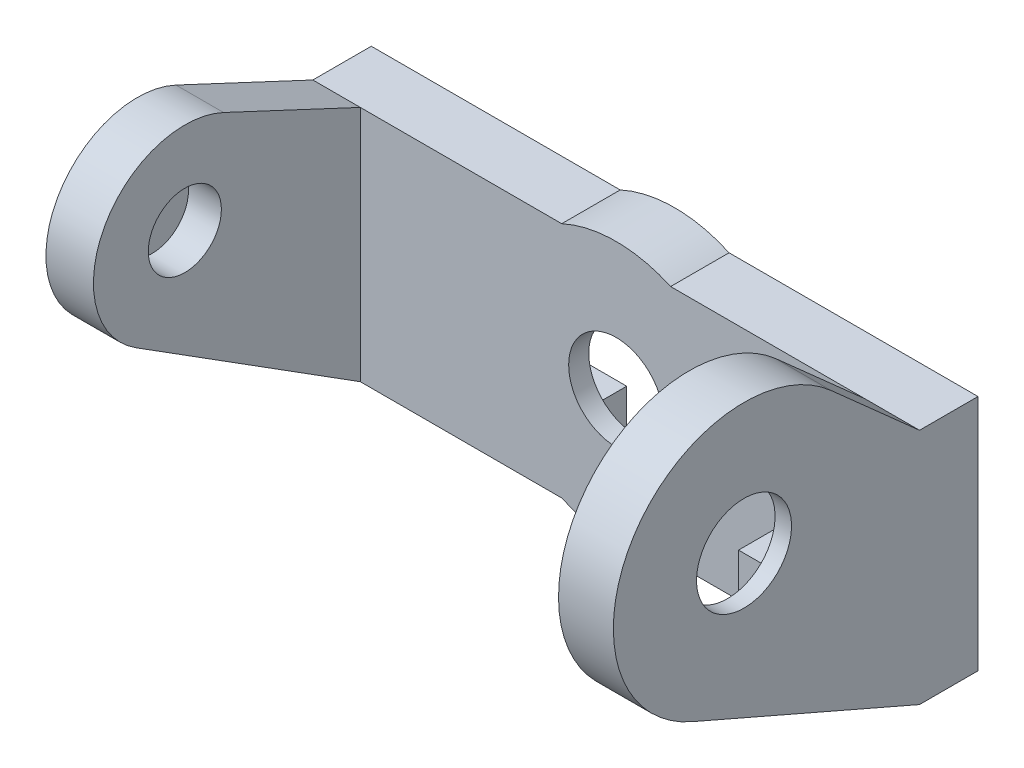
SolidWorks part; units mm, degrees
ref_plane "正面" through (0, 0, 0) normal (0, 0, 1) x (1, 0, 0)
ref_plane "平面" through (0, 0, 0) normal (0, 1, 0) x (1, 0, 0)
ref_plane "右側面" through (0, 0, 0) normal (1, 0, 0) x (0, 0, -1)
sketch "ｽｹｯﾁ1" plane through (0, 0, 0) normal (0, 0, 1) x (1, 0, 0)
  line L0 (0, 0) -> (13.6216, 0)
  line L1 (33.2, 0) -> (33.2, 13.0002)
  line L2 (33.2, 13.0002) -> (19.5784, 13.0002)
  line L3 (0, 13.0002) -> (0, 0)
  line L4 (16.6, 13.0002) -> (16.6, 0) construction
  line L5 (16.6, 6.5001) -> (33.2, 6.5001) construction
  line L6 (13.9218, 11.3099) -> (13.9218, 9.1783) construction
  line L7 (13.9218, 9.1783) -> (11.7902, 9.1783) construction
  line L8 (11.7902, 3.8219) -> (13.9218, 3.8219) construction
  line L9 (13.9218, 3.8219) -> (13.9218, 1.6903) construction
  line L10 (19.2782, 1.6903) -> (19.2782, 3.8219) construction
  line L11 (19.2782, 3.8219) -> (21.4098, 3.8219) construction
  line L12 (21.4098, 9.1783) -> (19.2782, 9.1783) construction
  line L13 (19.2782, 9.1783) -> (19.2782, 11.3099) construction
  line L14 (13.6216, 13.0002) -> (0, 13.0002)
  line L15 (19.5784, 0) -> (33.2, 0)
  arc A0 (19.5784, 13.0002) -> (13.6216, 13.0002) centre (16.6, 6.5001) ccw
  arc A1 (11.7902, 9.1783) -> (11.7902, 3.8219) centre (16.6, 6.5001) ccw construction
  arc A2 (13.9218, 1.6903) -> (19.2782, 1.6903) centre (16.6, 6.5001) ccw construction
  arc A3 (21.4098, 3.8219) -> (21.4098, 9.1783) centre (16.6, 6.5001) ccw construction
  arc A4 (19.2782, 11.3099) -> (13.9218, 11.3099) centre (16.6, 6.5001) ccw construction
  arc A5 (13.6216, 0) -> (19.5784, 0) centre (16.6, 6.5001) ccw
  dimension "D1" = 14.3
extrude "ﾎﾞｽ - 押し出し1" add sketch "ｽｹｯﾁ1" along normal blind 3.2
sketch "ｽｹｯﾁ2" plane through (0, 0, 0) normal (-1, 0, 0) x (0, 0, 1)
  line L3 (3.1997, 0) -> (15.472, 7.7447)
  line L4 (10.6849, 16.502) -> (3.1997, 13.0002)
  line L5 (3.1997, 13.0002) -> (3.1997, 0)
  arc A0 (15.472, 7.7447) -> (10.6849, 16.502) centre (12.8036, 11.9731) ccw
extrude "ﾎﾞｽ - 押し出し2" add sketch "ｽｹｯﾁ2" against normal blind 2.6
sketch "ｽｹｯﾁ3" plane through (33.2, 0, 0) normal (1, 0, 0) x (0, 0, -1)
  line L2 (-3.1997, 13.0002) -> (-8.0519, 17.3157)
  line L3 (-15.6549, 5.4162) -> (-3.1997, 0)
  line L5 (-3.1997, 13.0002) -> (-3.1997, 0)
  arc A0 (-8.0519, 17.3157) -> (-15.6549, 5.4162) centre (-12.8036, 11.9731) ccw
extrude "ﾎﾞｽ - 押し出し3" add sketch "ｽｹｯﾁ3" against normal blind 3
sketch "ｽｹｯﾁ4" plane through (0, 0, 0) normal (0, 0, -1) x (-1, 0, 0)
  line L0 (-19.2232, 11.2775) -> (-19.2232, 9.1233)
  line L1 (-19.2232, 9.1233) -> (-21.3773, 9.1233)
  line L2 (-21.3773, 3.8769) -> (-19.2232, 3.8769)
  line L3 (-19.2232, 3.8769) -> (-19.2232, 1.7228)
  line L4 (-13.9768, 1.7228) -> (-13.9768, 3.8769)
  line L5 (-13.9768, 3.8769) -> (-11.8227, 3.8769)
  line L6 (-19.2782, 11.3099) -> (-19.2782, 9.1783) construction
  line L7 (-19.2782, 9.1783) -> (-21.4098, 9.1783) construction
  line L8 (-21.4098, 3.8219) -> (-19.2782, 3.8219) construction
  line L9 (-19.2782, 3.8219) -> (-19.2782, 1.6903) construction
  line L10 (-13.9218, 1.6903) -> (-13.9218, 3.8219) construction
  line L11 (-13.9218, 3.8219) -> (-11.7902, 3.8219) construction
  line L12 (-11.7902, 9.1783) -> (-13.9218, 9.1783) construction
  line L13 (-13.9218, 9.1783) -> (-13.9218, 11.3099) construction
  line L14 (-11.8227, 9.1233) -> (-13.9768, 9.1233)
  line L15 (-13.9768, 9.1233) -> (-13.9768, 11.2775)
  arc A0 (-21.3773, 9.1233) -> (-21.3773, 3.8769) centre (-16.6, 6.5001) ccw
  arc A1 (-21.4098, 9.1783) -> (-21.4098, 3.8219) centre (-16.6, 6.5001) ccw construction
  arc A2 (-19.2782, 1.6903) -> (-13.9218, 1.6903) centre (-16.6, 6.5001) ccw construction
  arc A3 (-11.7902, 3.8219) -> (-11.7902, 9.1783) centre (-16.6, 6.5001) ccw construction
  arc A4 (-13.9218, 11.3099) -> (-19.2782, 11.3099) centre (-16.6, 6.5001) ccw construction
  arc A5 (-19.2232, 1.7228) -> (-13.9768, 1.7228) centre (-16.6, 6.5001) ccw
  arc A6 (-11.8227, 3.8769) -> (-11.8227, 9.1233) centre (-16.6, 6.5001) ccw
  arc A7 (-13.9768, 11.2775) -> (-19.2232, 11.2775) centre (-16.6, 6.5001) ccw
  dimension "D1" = 5.5051
  dimension "D2" = 0.055
extrude "ｶｯﾄ - 押し出し1" cut sketch "ｽｹｯﾁ4" against normal blind 2.1
sketch "ｽｹｯﾁ5" plane through (0, 0, 2.1) normal (0, 0, -1) x (-1, 0, 0)
  circle A0 centre (-16.6, 6.5001) radius 2.6
  dimension "D1" = 5.2
extrude "ｶｯﾄ - 押し出し2" cut sketch "ｽｹｯﾁ5" against normal up to vertex (1.1 mm away)
sketch "ｽｹｯﾁ6" plane through (30.2, 0, 0) normal (-1, 0, 0) x (0, 0, 1)
  line L3 (15.5036, 7.1241) -> (15.5036, 9.2731)
  line L4 (15.5036, 9.2731) -> (17.6526, 9.2731)
  line L5 (17.6526, 14.6731) -> (15.5036, 14.6731)
  line L6 (15.5036, 14.6731) -> (15.5036, 16.8221)
  line L7 (10.1036, 16.8221) -> (10.1036, 14.6731)
  line L8 (10.1036, 14.6731) -> (7.9546, 14.6731)
  line L9 (7.9546, 9.2731) -> (10.1036, 9.2731)
  line L10 (10.1036, 9.2731) -> (10.1036, 7.1241)
  arc A1 (17.6526, 9.2731) -> (17.6526, 14.6731) centre (12.8036, 11.9731) ccw
  arc A2 (15.5036, 16.8221) -> (10.1036, 16.8221) centre (12.8036, 11.9731) ccw
  arc A3 (7.9546, 14.6731) -> (7.9546, 9.2731) centre (12.8036, 11.9731) ccw
  arc A4 (10.1036, 7.1241) -> (15.5036, 7.1241) centre (12.8036, 11.9731) ccw
extrude "ｶｯﾄ - 押し出し3" cut sketch "ｽｹｯﾁ6" against normal blind 2.1
sketch "ｽｹｯﾁ7" plane through (32.3, 0, 0) normal (-1, 0, 0) x (0, 0, 1)
  circle A0 centre (12.8036, 11.9731) radius 2.6
  dimension "D1" = 5.2
extrude "ｶｯﾄ - 押し出し4" cut sketch "ｽｹｯﾁ7" against normal up to vertex (0.9 mm away)
sketch "ｽｹｯﾁ8" plane through (2.6, 0, 0) normal (1, 0, 0) x (0, 0, -1)
  circle A0 centre (-12.8036, 11.9731) radius 2
  dimension "D1" = 4
extrude "ｶｯﾄ - 押し出し5" cut sketch "ｽｹｯﾁ8" against normal blind 1.8
